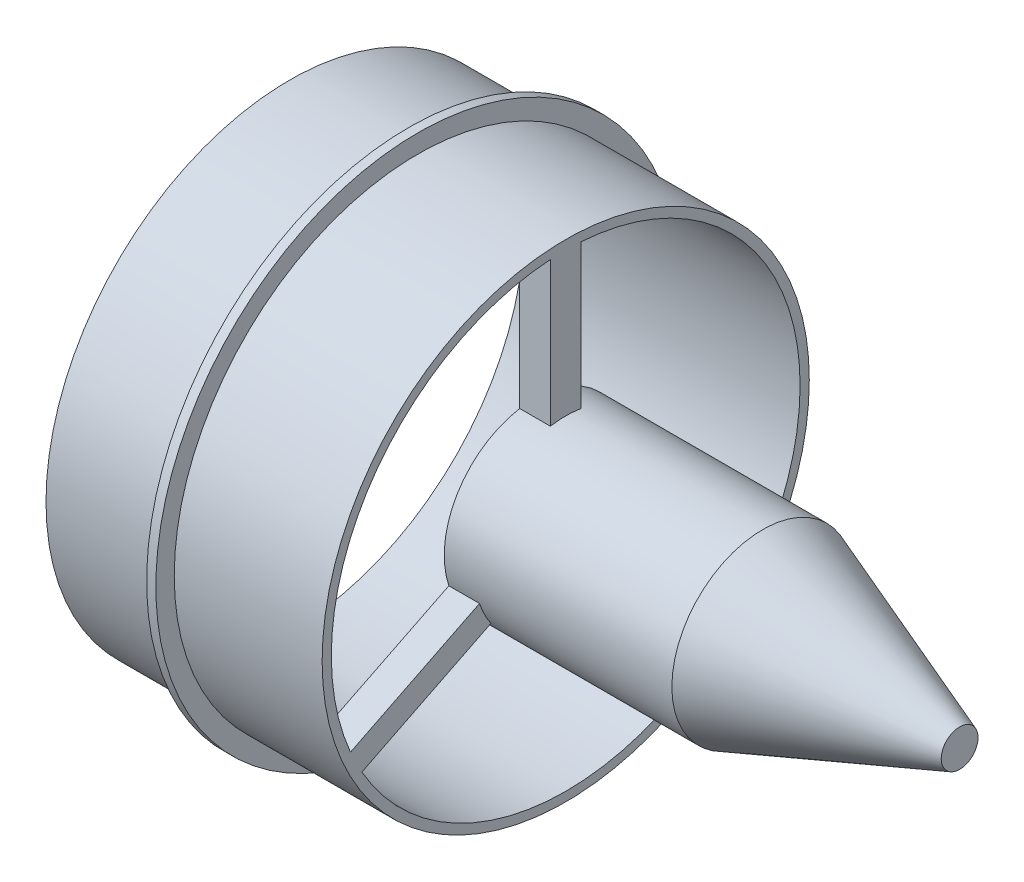
SolidWorks part; units mm, degrees
ref_plane "Спереди" through (0, 0, 0) normal (0, 0, 1) x (1, 0, 0)
ref_plane "Сверху" through (0, 0, 0) normal (0, 1, 0) x (1, 0, 0)
ref_plane "Справа" through (0, 0, 0) normal (1, 0, 0) x (0, 0, -1)
sketch "Эскиз1" plane through (0, 0, 0) normal (1, 0, 0) x (0, 0, -1)
  circle A0 centre (0, 0) radius 39.7
  dimension "D1" = 79.4
extrude "Бобышка-Вытянуть1" add sketch "Эскиз1" along normal blind 45 contours A0
sketch "Эскиз2" plane through (0, 0, 0) normal (-1, 0, 0) x (0, 0, 1)
  circle A0 centre (0, 0) radius 38.2
  dimension "D1" = 76.4
extrude "Вырез-Вытянуть1" cut sketch "Эскиз2" against normal through all
ref_plane "Плоскость4" through (19.4, 0, 0) normal (1, 0, 0) x (0, 0, -1)
sketch "Эскиз3" plane through (19.4, 0, 0) normal (1, 0, 0) x (0, 0, -1)
  circle A0 centre (0, 0) radius 39.7
  circle A1 centre (0, 0) radius 42.7
  dimension "D1" = 85.4
extrude "Бобышка-Вытянуть2" add sketch "Эскиз3" along normal blind 1.5
ref_plane "Плоскость5" through (45, 0, 0) normal (1, 0, 0) x (0, 0, -1)
sketch "Эскиз6" plane through (45, 0, 0) normal (1, 0, 0) x (0, 0, -1)
  line L1 (-2.5, 14.5873) -> (-2.5, 38.1181)
  line L2 (2.5, 14.5873) -> (2.5, 38.1181)
  line L4 (0, -55.0042) -> (0, 38.2) construction
  line L6 (-14.0464, -4.6623) -> (-35.0754, -15.1312)
  line L7 (-12.187, -8.3975) -> (-33.216, -18.8663)
  line L8 (-64.3822, 0) -> (49.2675, 0) construction
  line L9 (12.187, -8.3975) -> (33.216, -18.8663)
  line L10 (14.0464, -4.6623) -> (35.0754, -15.1312)
  arc A0 (-35.0754, -15.1312) -> (-33.216, -18.8663) centre (0, 0) ccw
  arc A1 (-12.187, -8.3975) -> (12.187, -8.3975) centre (0, 0) ccw
  arc A2 (-2.5, 14.5873) -> (-14.0464, -4.6623) centre (0, 0) ccw
  arc A3 (2.5, 38.1181) -> (-2.5, 38.1181) centre (0, 0) ccw
  arc A4 (35.0754, -15.1312) -> (33.216, -18.8663) centre (0, 0) cw
  arc A5 (14.0464, -4.6623) -> (2.5, 14.5873) centre (0, 0) ccw
  dimension "D1" = 76.4
  dimension "D2" = 29.6
  dimension "D3" = 2.5
  dimension "D4" = 2.5
  dimension "D5" = 4.1724
  dimension "D6" = 63.534
  dimension "D7" = 21.029
extrude "Бобышка-Вытянуть3" add sketch "Эскиз6" against normal blind 5
sketch "Эскиз7" plane through (45, 0, 0) normal (1, 0, 0) x (0, 0, -1)
  circle A0 centre (0, 0) radius 14.8
extrude "Бобышка-Вытянуть4" add sketch "Эскиз7" along normal blind 32.1
sketch "Эскиз9" plane through (77.1, 0, 0) normal (1, 0, 0) x (0, 0, -1)
  circle A0 centre (0, 0) radius 14.8
ref_plane "Плоскость6" through (109.2, 0, 0) normal (1, 0, 0) x (0, 0, -1)
sketch "Эскиз10" plane through (109.2, 0, 0) normal (1, 0, 0) x (0, 0, -1)
  circle A0 centre (0, 0) radius 3
  dimension "D1" = 6
loft "По сечениям1" add profiles "Эскиз9", "Эскиз10"
